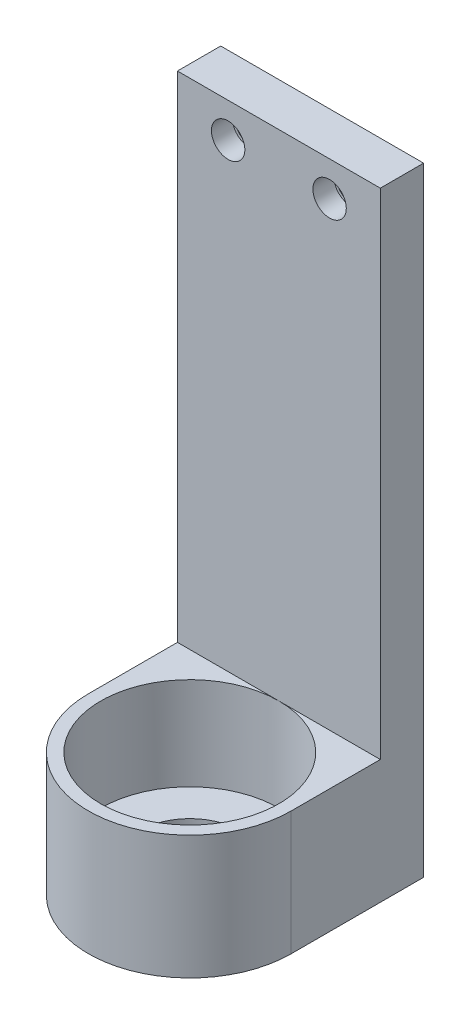
SolidWorks part; units mm, degrees
ref_plane "Front Plane" through (0, 0, 0) normal (0, 0, 1) x (1, 0, 0)
ref_plane "Top Plane" through (0, 0, 0) normal (0, 1, 0) x (1, 0, 0)
ref_plane "Right Plane" through (0, 0, 0) normal (1, 0, 0) x (0, 0, -1)
sketch "Sketch1" plane through (0, 0, 0) normal (0, 1, 0) x (1, 0, 0)
  line L0 (0, 21.4) -> (0, 16.4) construction
  line L2 (-16.4, 0) -> (-16.4, 21.4)
  line L3 (-16.4, 21.4) -> (16.4, 21.4)
  line L4 (16.4, 0) -> (16.4, 21.4)
  circle A0 centre (0, 0) radius 8.1
  circle A1 centre (0, 0) radius 14.4 construction
  arc A2 (-16.4, 0) -> (16.4, 0) centre (0, 0) ccw
  arc A3 (-16.4, 0) -> (16.4, 0) centre (0, 0) cw construction
  dimension "D1" = 16.2
  dimension "D2" = 28.8
  dimension "D3" = 32.8
extrude "Boss-Extrude1" add sketch "Sketch1" along normal blind 100
sketch "Sketch2" plane through (0, 100, 0) normal (0, 1, 0) x (1, 0, 0)
  circle A0 centre (0, 0) radius 14.4
  dimension "D1" = 28.8
extrude "Cut-Extrude1" cut sketch "Sketch2" against normal blind 80
sketch "Sketch3" plane through (0, 100, 0) normal (0, 1, 0) x (1, 0, 0)
  line L0 (0, 14.4) -> (-16.4, 14.4) construction
  line L1 (-16.4, 21.4) -> (-16.4, 0) construction
  line L2 (-16.4, 14.4) -> (-16.4, 0) construction
  line L3 (0, 14.4) -> (0, -16.4) construction
  line L4 (-16.4, 0) -> (-16.4, 14.4)
  line L5 (-16.4, 14.4) -> (16.4, 14.4)
  line L6 (16.4, 0) -> (16.4, 14.4)
  circle A0 centre (0, 0) radius 14.4 construction
  circle A1 centre (0, 0) radius 14.4 construction
  arc A3 (-16.4, 0) -> (16.4, 0) centre (0, 0) ccw
extrude "Cut-Extrude2" cut sketch "Sketch3" against normal blind 80
sketch "Sketch4" plane through (0, 20, 0) normal (0, 1, 0) x (1, 0, 0)
  circle A0 centre (0, 0) radius 14.4
  dimension "D1" = 28.8
extrude "Cut-Extrude3" cut sketch "Sketch4" against normal blind 15
sketch "Sketch5" plane through (0, 0, -14.4) normal (0, 0, 1) x (1, 0, 0)
  line L0 (0, 100) -> (0, 20) construction
  line L1 (16.4, 100) -> (-16.4, 100) construction
  line L2 (16.4, 20) -> (-16.4, 20) construction
  line L3 (0, 20) -> (-16.4, 60) construction
  line L4 (-16.4, 20) -> (-16.4, 100) construction
  line L5 (-16.4, 60) -> (16.4, 60) construction
  line L6 (16.4, 20) -> (16.4, 100) construction
  line L7 (-16.4, 100) -> (0, 100) construction
  line L8 (-16.4, 100) -> (-13.9, 100)
  line L9 (-16.4, 100) -> (-16.4, 97.5)
  line L10 (-16.4, 97.5) -> (-13.9, 97.5)
  line L11 (-13.9, 100) -> (-13.9, 97.5)
  line L12 (-8.2, 100) -> (-8.2, 60) construction
  line L14 (-2.5, 91.3218) -> (-13.9, 91.3218)
  line L15 (-2.5, 91.3218) -> (-2.5, 97.5)
  line L16 (-2.5, 97.5) -> (-13.9, 97.5)
  line L17 (-13.9, 91.3218) -> (-13.9, 97.5)
  line L18 (-2.5, 91.3218) -> (-13.9, 97.5) construction
  line L19 (-2.5, 97.5) -> (-13.9, 91.3218) construction
  point P18 (-8.2, 94.4109)
  point P23 (8.2, 94.4109)
  dimension "D1" = 2.5
hole_wizard "CBORE for M4 SHCS1" positions "Sketch5" profile "Sketch6" counterbore size "M4" standard "ANSI Metric" end condition through all
sketch "Sketch6" plane through (8.2, 94.4109, -14.4) normal (1, 0, 0) x (0, -1, 0)
  line L0 (0, 0) -> (0, 7)
  line L1 (0, 7) -> (2.25, 7)
  line L3 (2.25, 7) -> (2.25, 3.4)
  line L4 (2.25, 3.4) -> (2.7, 3.4)
  line L5 (2.7, 3.4) -> (2.7, 0)
  line L7 (2.7, 0) -> (0, 0)
  line L11 (0, -6.35) -> (0, 107.95) construction
  dimension "Thru Hole Dia." = 4.5
  dimension "Thru Hole Depth" = 7
  dimension "C'Bore Dia." = 5.4
  dimension "C'Bore Depth" = 3.4
